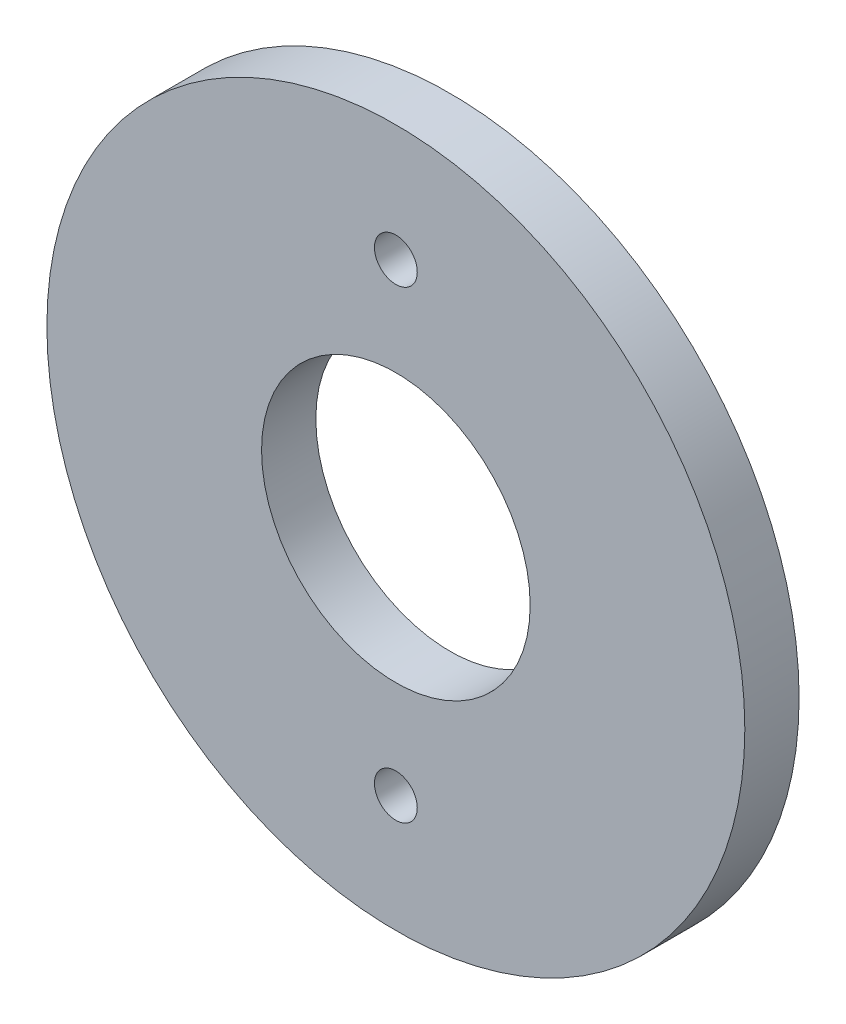
SolidWorks part; units mm, degrees
material "Cedar"
ref_plane "Front Plane" through (0, 0, 0) normal (0, 0, 1) x (1, 0, 0)
ref_plane "Top Plane" through (0, 0, 0) normal (0, 1, 0) x (1, 0, 0)
ref_plane "Right Plane" through (0, 0, 0) normal (1, 0, 0) x (0, 0, -1)
sketch "Sketch1" plane through (0, 0, 0) normal (0, 0, 1) x (1, 0, 0)
  circle A0 centre (0, 0) radius 28.575
  circle A1 centre (0, 0) radius 10.9982
  circle A2 centre (0, 18.9992) radius 1.7526
  circle A3 centre (0, -18.9992) radius 1.7526
  dimension "D1" = 57.15
  dimension "D2" = 21.9964
  dimension "D3" = 3.5052
  dimension "D5" = 3.5052
  dimension "D4" = 18.9992
  dimension "D6" = 18.9992
extrude "Boss-Extrude1" add sketch "Sketch1" along normal blind 4.445
